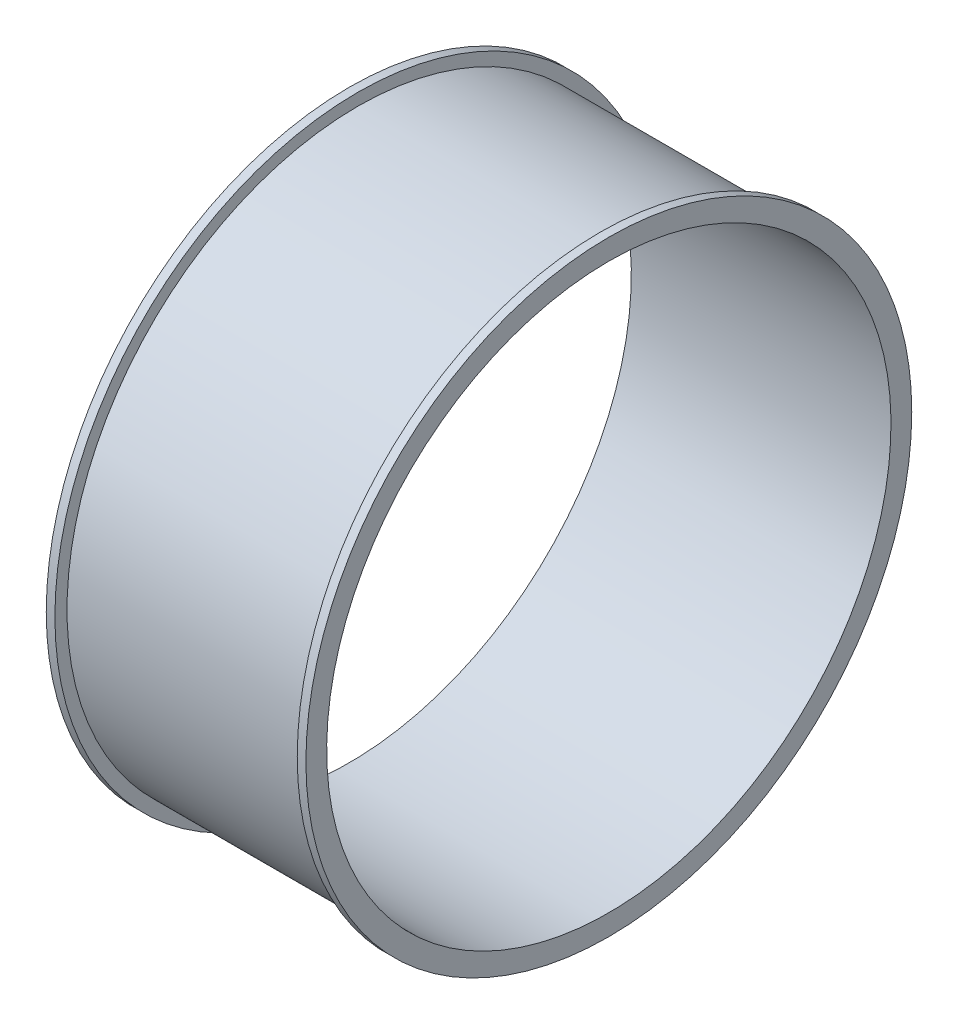
SolidWorks part; units mm, degrees
ref_plane "Front Plane" through (0, 0, 0) normal (0, 0, 1) x (1, 0, 0)
ref_plane "Top Plane" through (0, 0, 0) normal (0, 1, 0) x (1, 0, 0)
ref_plane "Right Plane" through (0, 0, 0) normal (1, 0, 0) x (0, 0, -1)
sketch "Sketch1" plane through (0, 0, 0) normal (0, 0, 1) x (1, 0, 0)
  line L0 (0, 0) -> (3000, 0) construction
  line L1 (700, 1630) -> (700, 1750)
  line L2 (700, 1750) -> (750, 1750)
  line L3 (750, 1750) -> (750, 1680)
  line L4 (750, 1680) -> (2150, 1680)
  line L5 (2150, 1680) -> (2150, 1750)
  line L6 (2150, 1750) -> (2200, 1750)
  line L7 (2200, 1750) -> (2200, 1630)
  line L8 (2200, 1630) -> (700, 1630)
revolve "Revolve1" add sketch "Sketch1" angle 360 about L0
